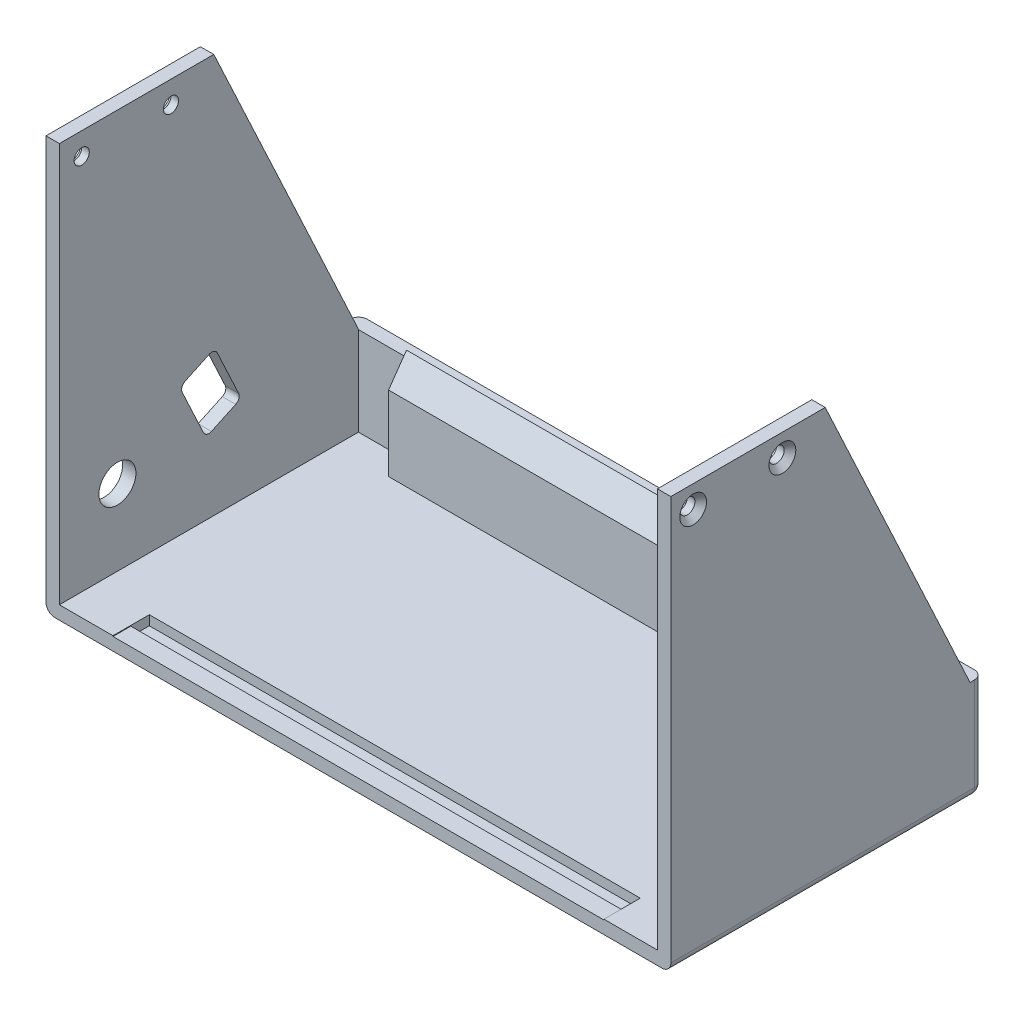
SolidWorks part; units mm, degrees
ref_plane "Piano frontale" through (0, 0, 0) normal (0, 0, 1) x (1, 0, 0)
ref_plane "Piano superiore" through (0, 0, 0) normal (0, 1, 0) x (1, 0, 0)
ref_plane "Piano destro" through (0, 0, 0) normal (1, 0, 0) x (0, 0, -1)
sketch "Schizzo1" plane through (0, 0, 0) normal (0, 1, 0) x (1, 0, 0)
  line L1 (0, 0) -> (-140, 0)
  line L2 (0, 0) -> (0, -70)
  line L3 (0, -70) -> (-140, -70)
  line L4 (-140, 0) -> (-140, -70)
  dimension "D1" = 140
  dimension "D2" = 70
extrude "Estrusione-Estrusione1" add sketch "Schizzo1" along normal blind 3
ref_plane "Piano1" through (-15, 0, 0) normal (1, 0, 0) x (0, 0, -1)
sketch "Schizzo2" plane through (-15, 0, 0) normal (1, 0, 0) x (0, 0, -1)
  line L3 (-70, 3) -> (0, 3) construction
  line L5 (-8.2406, 3) -> (-8.2406, 19.7942)
  line L6 (-8.2406, 19.7942) -> (-4.2256, 25.5283)
  line L7 (-4.2256, 25.5283) -> (-3, 22.9)
  line L8 (-3, 22.9) -> (-3, 3)
  line L9 (-8.2406, 3) -> (-3, 3)
  line L10 (0, 3) -> (0, 0) construction
  dimension "D1" = 155
  dimension "D2" = 19.9
  dimension "D3" = 60
  dimension "D4" = 3
  dimension "D5" = 7
  dimension "D6" = 2.9
extrude "Estrusione-Estrusione2" add sketch "Schizzo2" against normal blind 110 contours L7 L8 L9 L5 L6
sketch "Schizzo4" plane through (0, 0, 0) normal (1, 0, 0) x (0, 0, -1)
  line L1 (0, 3) -> (-3, 3)
  line L2 (0, 3) -> (0, 22.9)
  line L3 (0, 22.9) -> (-3, 22.9)
  line L4 (-3, 3) -> (-3, 22.9)
extrude "Estrusione-Estrusione3" add sketch "Schizzo4" against normal blind 140
sketch "Schizzo5" plane through (0, 3, 0) normal (0, 1, 0) x (1, 0, 0)
  line L0 (-140, -3) -> (-125, -3) construction
  line L1 (-140, -70) -> (-137, -70)
  line L2 (-140, -70) -> (-140, -3)
  line L3 (-140, -3) -> (-137, -3)
  line L4 (-137, -70) -> (-137, -3)
  line L6 (0, -70) -> (-3, -70)
  line L7 (0, -70) -> (0, -3)
  line L8 (0, -3) -> (-3, -3)
  line L9 (-3, -70) -> (-3, -3)
  line L10 (0, -70) -> (0, -3) construction
  dimension "D1" = 3
  dimension "D2" = 3
extrude "Estrusione-Estrusione4" add sketch "Schizzo5" along normal blind 89.5 contours L9 L8 L7 L6 | L4 L3 L2 L1
sketch "Schizzo6" plane through (-140, 0, 0) normal (-1, 0, 0) x (0, 0, 1)
  line L0 (3, 23) -> (35.4084, 92.5)
  line L3 (3, 23) -> (3, 92.5)
  line L4 (3, 92.5) -> (35.4084, 92.5)
  dimension "D1" = 69.5
  dimension "D2" = 65
extrude "Taglio-Estrusione1" cut sketch "Schizzo6" against normal up to surface (140 mm away) up to face at (0, 38.4667, 24.3333)
ref_plane "Piano2" through (-125, 0, 0) normal (-1, 0, 0) x (0, 0, 1)
sketch "Schizzo7" plane through (-125, 0, 0) normal (-1, 0, 0) x (0, 0, 1)
  line L1 (70, 92.5) -> (70, 0) construction
  line L3 (0, 0) -> (70, 0) construction
  line L6 (61.85, 3) -> (70, 3)
  line L9 (61.85, 3) -> (61.85, 0.85)
  line L11 (70, 2.85) -> (70, 3)
  line L12 (61.85, 0.85) -> (66, 0.85)
  line L13 (66, 0.85) -> (66, 2.85)
  line L14 (66, 2.85) -> (70, 2.85)
  dimension "D1" = 3
  dimension "D2" = 2.15
  dimension "D3" = 8.15
  dimension "D4" = 0.15
  dimension "D5" = 4
extrude "Taglio-Estrusione3" cut sketch "Schizzo7" against normal blind 110 contours L6 L11 L14 L13 L12 L9
fillet "Raccordo1" radius 2 5 edges at (0, 0, 35) (0, 11.45, 0) (-140, 0, 35) (-70, 0, 0) (-140, 11.45, 0)
sketch "Schizzo8" plane through (-140, 0, 0) normal (-1, 0, 0) x (0, 0, 1)
  line L0 (70, 92.5) -> (35.4084, 92.5) construction
  line L1 (70, 92.5) -> (70, 2) construction
  circle A0 centre (45, 87.5) radius 1.7
  circle A1 centre (65, 87.5) radius 1.7
  dimension "D1" = 3.4
  dimension "D2" = 3.4
  dimension "D3" = 5
  dimension "D5" = 5
  dimension "D4" = 20
extrude "Taglio-Estrusione4" cut sketch "Schizzo8" against normal through all contours A0 | A1
sketch "Schizzo10" plane through (-140, 0, 0) normal (-1, 0, 0) x (0, 0, 1)
  circle A0 centre (45, 87.5) radius 3
  circle A1 centre (65, 87.5) radius 3
  dimension "D1" = 6
  dimension "D2" = 6
extrude "Taglio-Estrusione5" cut sketch "Schizzo10" against normal blind 2 draft 45
sketch "Schizzo11" plane through (0, 0, 0) normal (1, 0, 0) x (0, 0, -1)
  circle A0 centre (-65, 87.5) radius 3
  circle A1 centre (-45, 87.5) radius 3
  dimension "D1" = 6
  dimension "D2" = 6
extrude "Taglio-Estrusione6" cut sketch "Schizzo11" against normal blind 2 draft 45
sketch "Schizzo12" plane through (-140, 0, 0) normal (-1, 0, 0) x (0, 0, 1)
  line L0 (37.7244, 20.2587) -> (42.5, 30.5)
  line L3 (41.847, 32.2941) -> (36.4092, 34.8298)
  line L4 (35.9304, 19.6057) -> (30.4925, 22.1415)
  line L5 (29.8395, 23.9355) -> (34.6151, 34.1768)
  line L6 (70, 92.5) -> (70, 2) construction
  line L7 (3, 23) -> (35.4084, 92.5) construction
  line L8 (2, 2) -> (70, 2) construction
  arc A2 (42.5, 30.5) -> (41.847, 32.2941) centre (41.2765, 31.0705) ccw
  arc A3 (37.7244, 20.2587) -> (35.9304, 19.6057) centre (36.5009, 20.8293) cw
  arc A4 (30.4925, 22.1415) -> (29.8395, 23.9355) centre (31.0631, 23.365) cw
  arc A5 (34.6151, 34.1768) -> (36.4092, 34.8298) centre (35.8386, 33.6062) cw
  dimension "D1" = 14
  dimension "D8" = 28.5
  dimension "D3" = 27.5
  dimension "D2" = 6
  dimension "D4" = 1.35
  dimension "D5" = 1.35
  dimension "D6" = 1.35
  dimension "D7" = 1.35
  dimension "D9" = 90
extrude "Taglio-Estrusione7" cut sketch "Schizzo12" against normal blind 3 contours L0 A2 L3 A5 L5 A4 L4 A3
sketch "Schizzo13" plane through (-140, 0, 0) normal (-1, 0, 0) x (0, 0, 1)
  line L0 (70, 92.5) -> (70, 2) construction
  line L1 (70, 0) -> (2, 0) construction
  circle A0 centre (57, 20) radius 4.15
  dimension "D1" = 8.3
  dimension "D2" = 13
  dimension "D3" = 20
extrude "Taglio-Estrusione8" cut sketch "Schizzo13" against normal blind 10
